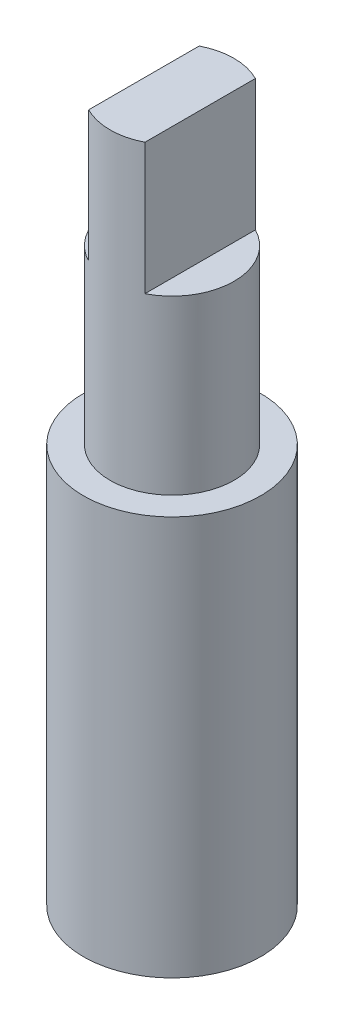
SolidWorks part; units mm, degrees
ref_plane "Front Plane" through (0, 0, 0) normal (0, 0, 1) x (1, 0, 0)
ref_plane "Top Plane" through (0, 0, 0) normal (0, 1, 0) x (1, 0, 0)
ref_plane "Right Plane" through (0, 0, 0) normal (1, 0, 0) x (0, 0, -1)
sketch "Sketch1" plane through (0, 0, 0) normal (0, 1, 0) x (1, 0, 0)
  circle A0 centre (0, 0) radius 3.075
  dimension "D1" = 6.15
extrude "Boss-Extrude1" add sketch "Sketch1" along normal blind 13.85
sketch "Sketch2" plane through (0, 13.85, 0) normal (0, 1, 0) x (1, 0, 0)
  circle A0 centre (0, 0) radius 2.15
  dimension "D1" = 4.3
extrude "Boss-Extrude2" add sketch "Sketch2" along normal blind 5.98
sketch "Sketch3" plane through (0, 19.83, 0) normal (0, 1, 0) x (1, 0, 0)
  line L0 (-0.975, 1.9162) -> (-0.975, -1.9162)
  line L1 (0.975, 1.9162) -> (0.975, -1.9162)
  circle A0 centre (0, 0) radius 2.15 construction
  circle A1 centre (0, 0) radius 2.15 construction
  arc A2 (-0.975, -1.9162) -> (0.975, -1.9162) centre (0, 0) ccw
  arc A3 (0.975, 1.9162) -> (-0.975, 1.9162) centre (0, 0) ccw
  point P4 (-2.15, 0)
  point P5 (2.15, 0)
  dimension "D1" = 1.95
  dimension "D2" = 0.975
extrude "Boss-Extrude3" add sketch "Sketch3" along normal blind 4.55
sketch "Sketch4" plane through (0, 0, 0) normal (0, -1, 0) x (1, 0, 0)
  circle A0 centre (0, 0) radius 2.15
  dimension "D1" = 4.3
extrude "Cut-Extrude1" cut sketch "Sketch4" against normal blind 1.95
